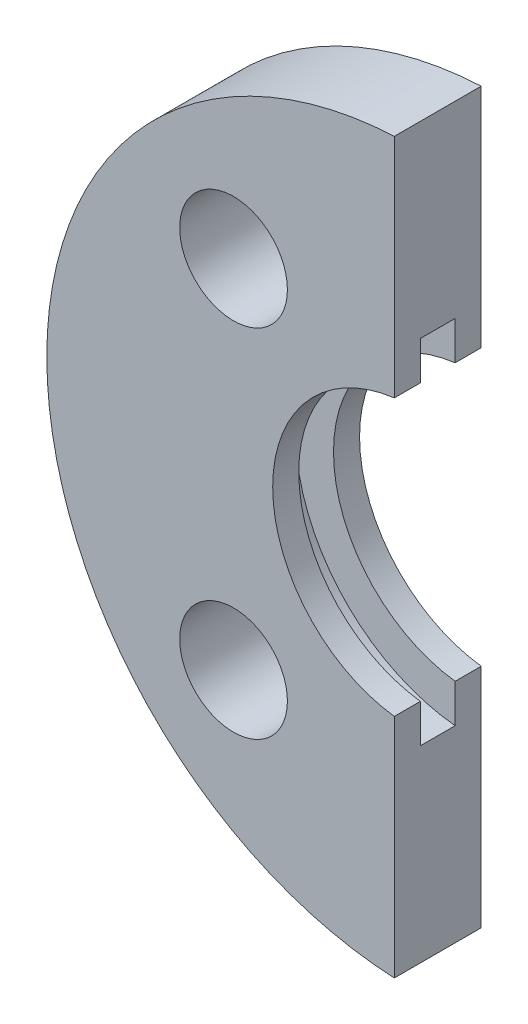
SolidWorks part; units mm, degrees
ref_plane "前视基准面" through (0, 0, 0) normal (0, 0, 1) x (1, 0, 0)
ref_plane "上视基准面" through (0, 0, 0) normal (0, 1, 0) x (1, 0, 0)
ref_plane "右视基准面" through (0, 0, 0) normal (1, 0, 0) x (0, 0, -1)
sketch "草图1" plane through (0, 0, 0) normal (0, 0, 1) x (1, 0, 0)
  line L5 (-10.253, -10.253) -> (10.253, 10.253) construction
  line L6 (-10.253, 10.253) -> (10.253, -10.253) construction
  circle A0 centre (-10.253, 10.253) radius 3.1
  circle A1 centre (10.253, 10.253) radius 3.1
  circle A2 centre (-10.253, -10.253) radius 3.1
  circle A3 centre (10.253, -10.253) radius 3.1
  circle A4 centre (0, 0) radius 21
  circle A5 centre (0, 0) radius 8
  point P0 (0, 0)
  point P6 (0, 0)
  point P16 (0, 0)
extrude "凸台-拉伸1" add sketch "草图1" along normal blind 5
sketch "草图2" plane through (0, 0, 5) normal (0, 0, 1) x (1, 0, 0)
  line L1 (-1, 0) -> (-1, 23.542)
  line L2 (-1, 23.542) -> (27.7591, 23.542)
  line L3 (27.7591, 23.542) -> (27.7591, -27.3088)
  line L4 (27.7591, -27.3088) -> (-1, -27.3088)
  line L5 (-1, -27.3088) -> (-1, 0)
extrude "切除-拉伸1" cut sketch "草图2" against normal blind 10
sketch "草图3" plane through (-1, 0, 0) normal (1, 0, 0) x (0, 0, -1)
  line L0 (-5, 7.9373) -> (0, 7.9373) construction
  line L1 (-3.5, 7.2097) -> (-1.5, 7.2097)
  line L2 (-3.5, 7.2097) -> (-3.5, 8.6648)
  line L3 (-3.5, 8.6648) -> (-1.5, 8.6648)
  line L4 (-1.5, 7.2097) -> (-1.5, 8.6648)
  line L5 (-3.5, 7.2097) -> (-1.5, 8.6648) construction
  line L6 (-3.5, 8.6648) -> (-1.5, 7.2097) construction
  point P0 (-2.5, 7.9373)
  point P7 (-1.4857, 8.984)
  point P8 (-1.4857, 8.6648)
extrude "切除-拉伸2" cut sketch "草图3" against normal blind 2
sketch "草图4" plane through (0, 0, 1.5) normal (0, 0, 1) x (1, 0, 0)
  circle A0 centre (0, 0) radius 10.2
extrude "切除-拉伸3" cut sketch "草图4" along normal blind 2
